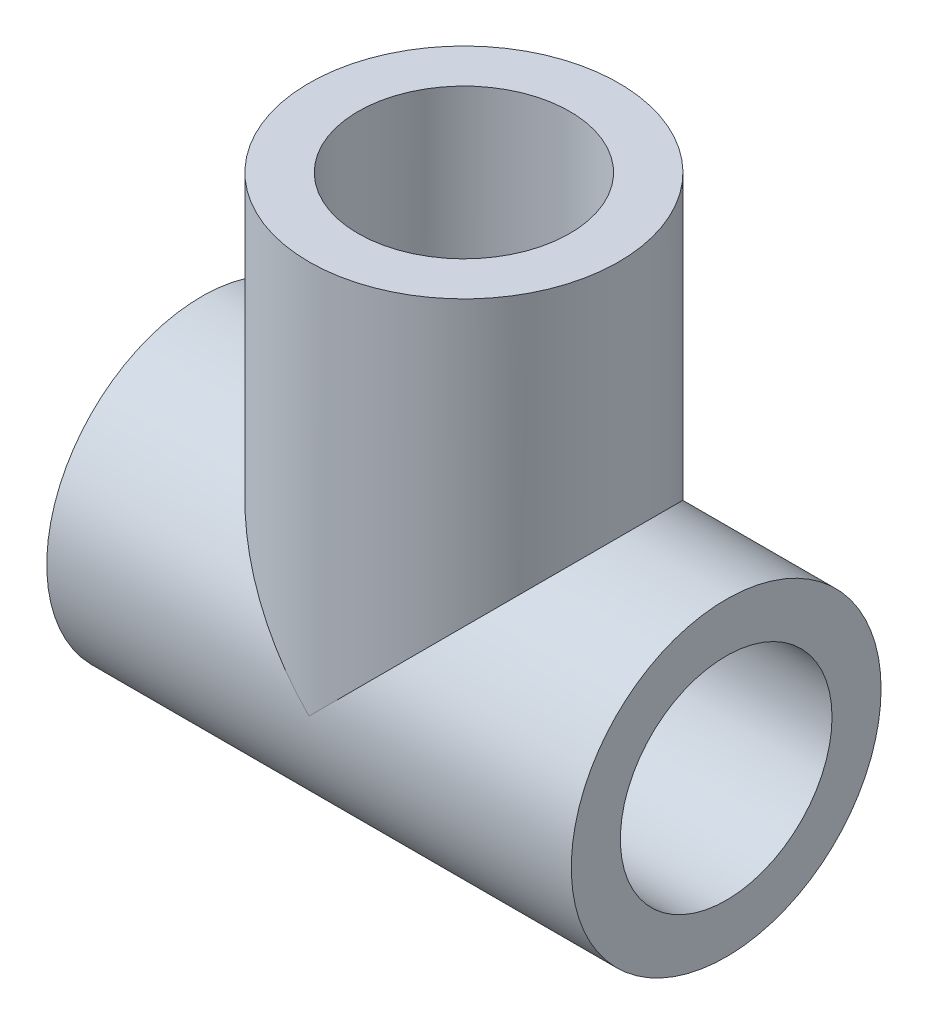
SolidWorks part; units mm, degrees
material "Nylon 101"
ref_plane "Front Plane" through (0, 0, 0) normal (0, 0, 1) x (1, 0, 0)
ref_plane "Top Plane" through (0, 0, 0) normal (0, 1, 0) x (1, 0, 0)
ref_plane "Right Plane" through (0, 0, 0) normal (1, 0, 0) x (0, 0, -1)
sketch "Sketch1" plane through (0, 0, 0) normal (1, 0, 0) x (0, 0, -1)
  circle A0 centre (0, 0) radius 7.5
  dimension "D2" = 15
extrude "Boss-Extrude1" add sketch "Sketch1" along normal blind 25.4
sketch "Sketch2" plane through (0, 0, 0) normal (0, 1, 0) x (1, 0, 0)
  line L0 (25.4, 7.5) -> (0, 7.5) construction
  circle A1 centre (12.7, 0) radius 7.5
  dimension "D1" = 12.7
extrude "Boss-Extrude2" add sketch "Sketch2" along normal blind 19.05
sketch "Sketch3" plane through (25.4, 0, 0) normal (1, 0, 0) x (0, 0, -1)
  circle A0 centre (0, 0) radius 5.125
  dimension "D1" = 10.25
extrude "Cut-Extrude1" cut sketch "Sketch3" against normal through all
sketch "Sketch4" plane through (0, 19.05, 0) normal (0, 1, 0) x (1, 0, 0)
  circle A0 centre (12.7, 0) radius 5.125
  dimension "D1" = 10.25
extrude "Cut-Extrude2" cut sketch "Sketch4" against normal up to next
